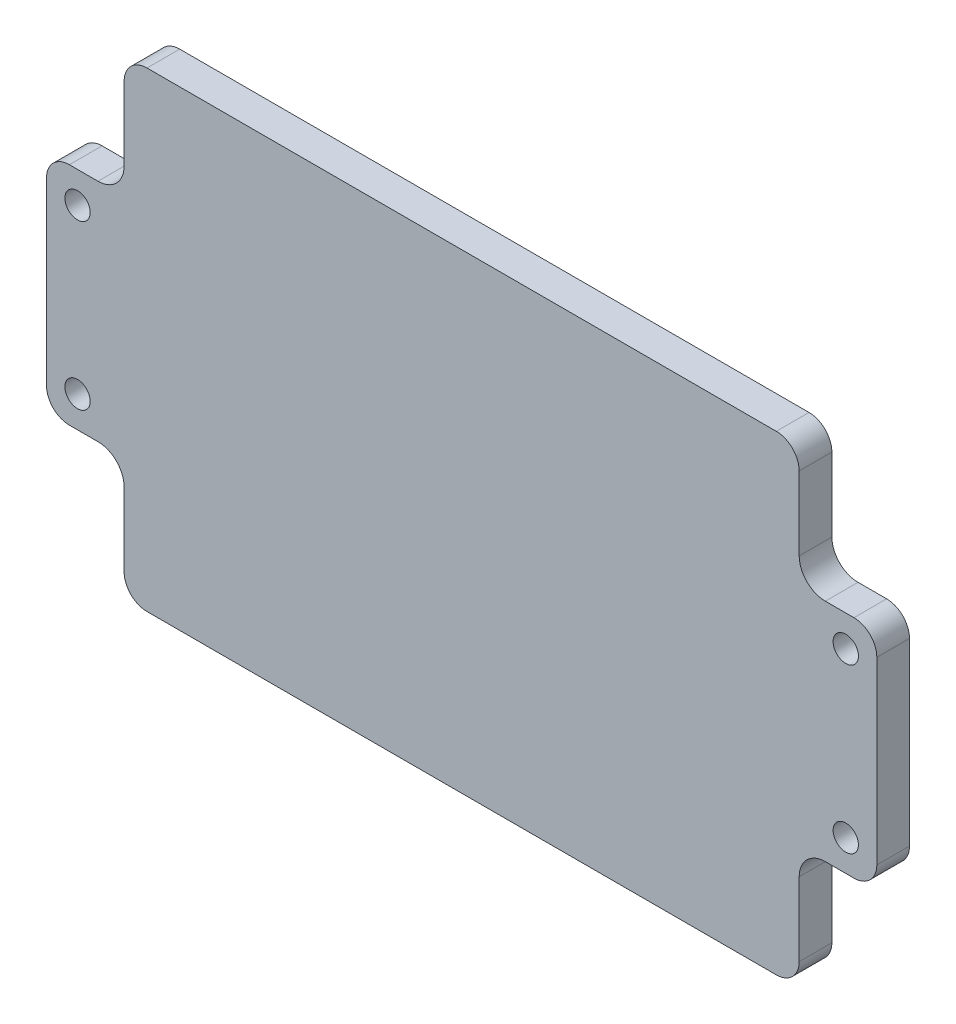
SolidWorks part; units mm, degrees
ref_plane "前视基准面" through (0, 0, 0) normal (0, 0, 1) x (1, 0, 0)
ref_plane "上视基准面" through (0, 0, 0) normal (0, 1, 0) x (1, 0, 0)
ref_plane "右视基准面" through (0, 0, 0) normal (1, 0, 0) x (0, 0, -1)
other "Configuration Table"
sketch "草图1" plane through (0, 0, 0) normal (0, 0, 1) x (1, 0, 0)
  line L12 (0, 40) -> (0, 18) construction
  line L13 (0, 0) -> (102, 0) construction
  line L14 (0, 0) -> (0, 58) construction
  line L15 (0, 58) -> (102, 58) construction
  line L16 (102, 0) -> (102, 58) construction
  line L17 (3, 15) -> (6.5, 15) construction
  line L18 (9.5, 12) -> (9.5, 3) construction
  line L19 (12.5, 0) -> (89.5, 0) construction
  line L20 (92.5, 3) -> (92.5, 12) construction
  line L21 (95.5, 15) -> (99, 15) construction
  line L22 (102, 18) -> (102, 40) construction
  line L23 (99, 43) -> (95.5, 43) construction
  line L24 (92.5, 46) -> (92.5, 55) construction
  line L25 (89.5, 58) -> (12.5, 58) construction
  line L26 (9.5, 55) -> (9.5, 46) construction
  line L27 (6.5, 43) -> (3, 43) construction
  line L28 (0.2, 40) -> (0.2, 18)
  line L29 (3, 15.2) -> (6.5, 15.2)
  line L30 (9.7, 12) -> (9.7, 3)
  line L31 (12.5, 0.2) -> (89.5, 0.2)
  line L32 (92.3, 3) -> (92.3, 12)
  line L33 (95.5, 15.2) -> (99, 15.2)
  line L34 (101.8, 18) -> (101.8, 40)
  line L35 (99, 42.8) -> (95.5, 42.8)
  line L36 (92.3, 46) -> (92.3, 55)
  line L37 (89.5, 57.8) -> (12.5, 57.8)
  line L38 (9.7, 55) -> (9.7, 46)
  line L39 (6.5, 42.8) -> (3, 42.8)
  line L40 (0.2, 0.2) -> (101.8, 0.2) construction
  line L41 (101.8, 0.2) -> (101.8, 57.8) construction
  line L42 (0.2, 57.8) -> (101.8, 57.8) construction
  line L43 (0.2, 0.2) -> (0.2, 57.8) construction
  arc A0 (92.5, 55) -> (89.5, 58) centre (89.5, 55) ccw construction
  arc A1 (95.5, 43) -> (92.5, 46) centre (95.5, 46) cw construction
  arc A2 (102, 40) -> (99, 43) centre (99, 40) ccw construction
  arc A3 (99, 15) -> (102, 18) centre (99, 18) ccw construction
  arc A4 (92.5, 12) -> (95.5, 15) centre (95.5, 12) cw construction
  arc A5 (89.5, 0) -> (92.5, 3) centre (89.5, 3) ccw construction
  arc A6 (9.5, 3) -> (12.5, 0) centre (12.5, 3) ccw construction
  arc A7 (6.5, 15) -> (9.5, 12) centre (6.5, 12) cw construction
  arc A8 (0, 18) -> (3, 15) centre (3, 18) ccw construction
  arc A9 (0, 40) -> (3, 43) centre (3, 40) cw construction
  arc A10 (9.5, 46) -> (6.5, 43) centre (6.5, 46) cw construction
  arc A11 (12.5, 58) -> (9.5, 55) centre (12.5, 55) ccw construction
  arc A12 (0.2, 18) -> (3, 15.2) centre (3, 18) ccw
  arc A13 (6.5, 15.2) -> (9.7, 12) centre (6.5, 12) cw
  arc A14 (9.7, 3) -> (12.5, 0.2) centre (12.5, 3) ccw
  arc A15 (89.5, 0.2) -> (92.3, 3) centre (89.5, 3) ccw
  arc A16 (92.3, 12) -> (95.5, 15.2) centre (95.5, 12) cw
  arc A17 (99, 15.2) -> (101.8, 18) centre (99, 18) ccw
  arc A18 (101.8, 40) -> (99, 42.8) centre (99, 40) ccw
  arc A19 (95.5, 42.8) -> (92.3, 46) centre (95.5, 46) cw
  arc A20 (92.3, 55) -> (89.5, 57.8) centre (89.5, 55) ccw
  arc A21 (12.5, 57.8) -> (9.7, 55) centre (12.5, 55) ccw
  arc A22 (9.7, 46) -> (6.5, 42.8) centre (6.5, 46) cw
  arc A23 (0.2, 40) -> (3, 42.8) centre (3, 40) cw
  point P20 (92.5, 58)
  point P25 (102, 43)
  point P28 (102, 15)
  point P33 (92.5, 0)
  point P36 (9.5, 0)
  point P41 (0, 15)
  point P44 (0, 43)
  point P47 (9.5, 43)
  point P50 (9.5, 58)
  dimension "D11" = 3
  dimension "D1" = 102
  dimension "D2" = 58
  dimension "D3" = 15
  dimension "D4" = 9.5
  dimension "D5" = 9.5
  dimension "D6" = 15
  dimension "D7" = 15
  dimension "D8" = 15
  dimension "D9" = 9.5
  dimension "D10" = 9.5
  dimension "D12" = 0.2
extrude "凸台-拉伸1" add sketch "草图1" along normal blind 4
sketch "草图3" plane through (0, 0, 4) normal (0, 0, 1) x (1, 0, 0)
  line L0 (0.2, 29) -> (101.8, 29) construction
  line L1 (0.2, 40) -> (0.2, 18) construction
  line L2 (101.8, 18) -> (101.8, 40) construction
  circle A0 centre (4, 39) radius 1.55
  circle A1 centre (4, 19) radius 1.55
  circle A2 centre (98, 39) radius 1.55
  circle A3 centre (98, 19) radius 1.55
  point P14 (51, 29)
  point P16 (55, 29)
  dimension "D5" = 3.1
  dimension "D6" = 3.1
  dimension "D7" = 3.1
  dimension "D8" = 3.1
  dimension "D1" = 10
  dimension "D2" = 10
  dimension "D3" = 10
  dimension "D4" = 10
  dimension "D9" = 47
  dimension "D10" = 47
  dimension "D11" = 47
  dimension "D12" = 47
extrude "切除-拉伸1" cut sketch "草图3" against normal through all
shell "抽壳1" thickness 2
